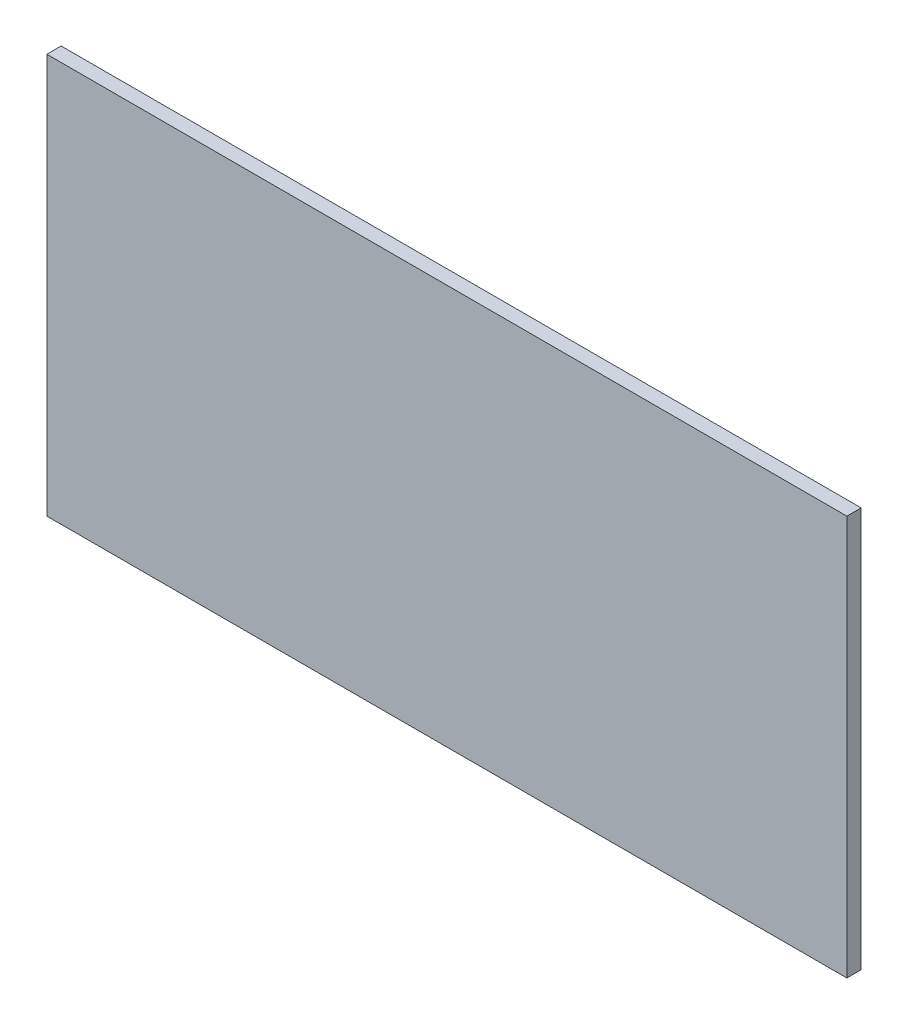
SolidWorks part; units mm, degrees
ref_plane "Front Plane" through (0, 0, 0) normal (0, 0, 1) x (1, 0, 0)
ref_plane "Top Plane" through (0, 0, 0) normal (0, 1, 0) x (1, 0, 0)
ref_plane "Right Plane" through (0, 0, 0) normal (1, 0, 0) x (0, 0, -1)
sketch "Sketch2" plane through (0, 0, 0) normal (0, 0, 1) x (1, 0, 0)
  line L1 (0, 0) -> (1400, 0)
  line L2 (0, 0) -> (0, 700)
  line L3 (0, 700) -> (1400, 700)
  line L4 (1400, 0) -> (1400, 700)
  dimension "D1" = 1400
  dimension "D2" = 700
extrude "Boss-Extrude1" add sketch "Sketch2" along normal blind 25
